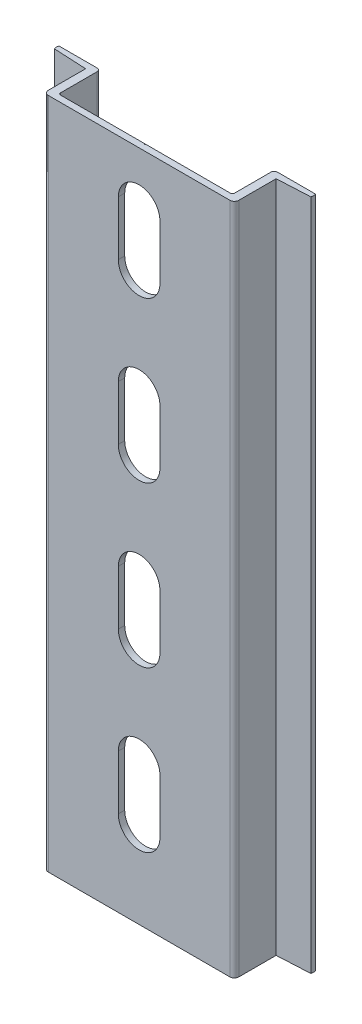
SolidWorks part; units mm, degrees
ref_plane "Alzado" through (0, 0, 0) normal (0, 0, 1) x (1, 0, 0)
ref_plane "Planta" through (0, 0, 0) normal (0, 1, 0) x (1, 0, 0)
ref_plane "Vista lateral" through (0, 0, 0) normal (1, 0, 0) x (0, 0, -1)
sketch "Croquis1" plane through (0, 0, 0) normal (0, 1, 0) x (1, 0, 0)
  line L0 (20.036, -8.0144) -> (20.036, 0) construction
  line L1 (34.92, -1.4884) -> (40.0721, -1.2268)
  line L3 (6.4521, -0.9884) -> (6.4521, -6.7144)
  line L4 (0, -0.4884) -> (5.9521, -0.4884)
  line L5 (5.8521, -8.0144) -> (34.22, -8.0144)
  line L6 (34.92, -1.4884) -> (34.92, -7.3144)
  line L8 (40.0721, -0.4884) -> (34.12, -0.4884)
  line L9 (33.62, -0.9884) -> (33.62, -6.7144)
  line L10 (5.1521, -1.4884) -> (5.1521, -7.3144)
  line L11 (6.7521, -7.0144) -> (33.32, -7.0144) construction
  line L12 (5.1521, -1.4884) -> (0, -1.2268)
  line L13 (6.7521, -7.0144) -> (33.32, -7.0144)
  arc A0 (34.22, -8.0144) -> (34.92, -7.3144) centre (34.22, -7.3144) ccw
  arc A1 (34.12, -0.4884) -> (33.62, -0.9884) centre (34.12, -0.9884) ccw
  arc A2 (33.32, -7.0144) -> (33.62, -6.7144) centre (33.32, -6.7144) ccw
  arc A3 (6.7521, -7.0144) -> (6.4521, -6.7144) centre (6.7521, -6.7144) cw
  arc A4 (5.9521, -0.4884) -> (6.4521, -0.9884) centre (5.9521, -0.9884) cw
  arc A5 (5.8521, -8.0144) -> (5.1521, -7.3144) centre (5.8521, -7.3144) cw
  spline S0 degree 2 poles (40.0721, -0.4884) (40.1909, -0.8585) (40.0721, -1.2268) knots 0 0 0 1 1 1
  spline S1 degree 2 poles (0, -0.4884) (-0.1188, -0.8585) (0, -1.2268) knots 0 0 0 1 1 1
extrude "Saliente-Extruir1" add sketch "Croquis1" along normal blind 105 and the other way blind 0.1
sketch "Croquis2" plane through (0, 0, 8.0144) normal (0, 0, 1) x (1, 0, 0)
  line L0 (20.036, -0.1) -> (20.036, 10) construction
  line L1 (5.8521, -0.1) -> (34.22, -0.1) construction
  line L2 (20.036, 25) -> (20.036, 35) construction
  line L3 (16.786, 38.25) -> (16.786, 46.75)
  line L4 (23.286, 38.25) -> (23.286, 46.75)
  line L5 (16.786, 13.25) -> (16.786, 21.75)
  line L6 (16.786, 63.25) -> (16.786, 71.75)
  line L7 (23.286, 13.25) -> (23.286, 21.75)
  line L8 (23.286, 63.25) -> (23.286, 71.75)
  line L9 (16.786, 88.25) -> (16.786, 96.75)
  line L10 (23.286, 88.25) -> (23.286, 96.75)
  line L11 (16.786, 113.25) -> (16.786, 121.75)
  line L12 (23.286, 113.25) -> (23.286, 121.75)
  line L13 (16.786, 138.25) -> (16.786, 146.75)
  line L14 (23.286, 138.25) -> (23.286, 146.75)
  line L15 (16.786, 163.25) -> (16.786, 171.75)
  line L16 (23.286, 163.25) -> (23.286, 171.75)
  line L17 (16.786, 188.25) -> (16.786, 196.75)
  line L18 (23.286, 188.25) -> (23.286, 196.75)
  arc A0 (23.286, 21.75) -> (16.786, 21.75) centre (20.036, 21.75) ccw
  arc A1 (16.786, 13.25) -> (23.286, 13.25) centre (20.036, 13.25) ccw
  arc A2 (23.286, 46.75) -> (16.786, 46.75) centre (20.036, 46.75) ccw
  arc A3 (16.786, 38.25) -> (23.286, 38.25) centre (20.036, 38.25) ccw
  arc A4 (23.286, 71.75) -> (16.786, 71.75) centre (20.036, 71.75) ccw
  arc A5 (16.786, 63.25) -> (23.286, 63.25) centre (20.036, 63.25) ccw
  arc A6 (23.286, 96.75) -> (16.786, 96.75) centre (20.036, 96.75) ccw
  arc A7 (16.786, 88.25) -> (23.286, 88.25) centre (20.036, 88.25) ccw
  arc A8 (23.286, 121.75) -> (16.786, 121.75) centre (20.036, 121.75) ccw
  arc A9 (16.786, 113.25) -> (23.286, 113.25) centre (20.036, 113.25) ccw
  arc A10 (23.286, 146.75) -> (16.786, 146.75) centre (20.036, 146.75) ccw
  arc A11 (16.786, 138.25) -> (23.286, 138.25) centre (20.036, 138.25) ccw
  arc A12 (23.286, 171.75) -> (16.786, 171.75) centre (20.036, 171.75) ccw
  arc A13 (16.786, 163.25) -> (23.286, 163.25) centre (20.036, 163.25) ccw
  arc A14 (23.286, 196.75) -> (16.786, 196.75) centre (20.036, 196.75) ccw
  arc A15 (16.786, 188.25) -> (23.286, 188.25) centre (20.036, 188.25) ccw
  point P10 (0, 0)
  dimension "D1" = 8
extrude "Cortar-Extruir4" cut sketch "Croquis2" against normal blind 10
sketch "Croquis4" plane through (0, 0, 7.0144) normal (0, 0, -1) x (-1, 0, 0)
  line L0 (-20.036, 10) -> (-20.036, -0.1) construction
  line L2 (-20.111, 24.95) -> (-19.961, 24.95)
  line L3 (-20.111, -0.05) -> (-19.961, -0.05)
  line L4 (-20.111, -0.05) -> (-20.111, 9.95)
  line L5 (-20.111, 9.95) -> (-19.961, 9.95)
  line L6 (-19.961, -0.05) -> (-19.961, 9.95)
  line L7 (-20.111, -0.05) -> (-19.961, 9.95) construction
  line L8 (-20.111, 9.95) -> (-19.961, -0.05) construction
  line L9 (-20.111, 24.95) -> (-20.111, 34.95)
  line L10 (-20.111, 34.95) -> (-19.961, 34.95)
  line L11 (-19.961, 24.95) -> (-19.961, 34.95)
  line L12 (-20.036, 35) -> (-20.036, 24.9) construction
  line L13 (-20.111, 24.95) -> (-19.961, 34.95) construction
  line L14 (-20.111, 34.95) -> (-19.961, 24.95) construction
  line L15 (-20.111, 49.95) -> (-19.961, 49.95)
  line L16 (-20.111, 49.95) -> (-20.111, 59.95)
  line L17 (-20.111, 59.95) -> (-19.961, 59.95)
  line L18 (-19.961, 49.95) -> (-19.961, 59.95)
  line L19 (-20.036, 60) -> (-20.036, 49.9) construction
  line L20 (-20.111, 49.95) -> (-19.961, 59.95) construction
  line L21 (-20.111, 59.95) -> (-19.961, 49.95) construction
  line L22 (-20.111, 74.95) -> (-19.961, 74.95)
  line L23 (-20.111, 74.95) -> (-20.111, 84.95)
  line L24 (-20.111, 84.95) -> (-19.961, 84.95)
  line L25 (-19.961, 74.95) -> (-19.961, 84.95)
  line L26 (-20.036, 85) -> (-20.036, 74.9) construction
  line L27 (-20.111, 74.95) -> (-19.961, 84.95) construction
  line L28 (-20.111, 84.95) -> (-19.961, 74.95) construction
  line L29 (-20.111, 99.95) -> (-19.961, 99.95)
  line L30 (-20.111, 99.95) -> (-20.111, 109.95)
  line L31 (-20.111, 109.95) -> (-19.961, 109.95)
  line L32 (-19.961, 99.95) -> (-19.961, 109.95)
  line L33 (-20.036, 110) -> (-20.036, 99.9) construction
  line L34 (-20.111, 99.95) -> (-19.961, 109.95) construction
  line L35 (-20.111, 109.95) -> (-19.961, 99.95) construction
  line L36 (-20.111, 124.95) -> (-19.961, 124.95)
  line L37 (-20.111, 124.95) -> (-20.111, 134.95)
  line L38 (-20.111, 134.95) -> (-19.961, 134.95)
  line L39 (-19.961, 124.95) -> (-19.961, 134.95)
  line L40 (-20.036, 135) -> (-20.036, 124.9) construction
  line L41 (-20.111, 124.95) -> (-19.961, 134.95) construction
  line L42 (-20.111, 134.95) -> (-19.961, 124.95) construction
  line L43 (-20.111, 149.95) -> (-19.961, 149.95)
  line L44 (-20.111, 149.95) -> (-20.111, 159.95)
  line L45 (-20.111, 159.95) -> (-19.961, 159.95)
  line L46 (-19.961, 149.95) -> (-19.961, 159.95)
  line L47 (-20.036, 160) -> (-20.036, 149.9) construction
  line L48 (-20.111, 149.95) -> (-19.961, 159.95) construction
  line L49 (-20.111, 159.95) -> (-19.961, 149.95) construction
  line L50 (-20.111, 174.95) -> (-19.961, 174.95)
  line L51 (-20.111, 174.95) -> (-20.111, 184.95)
  line L52 (-20.111, 184.95) -> (-19.961, 184.95)
  line L53 (-19.961, 174.95) -> (-19.961, 184.95)
  line L54 (-20.036, 185) -> (-20.036, 174.9) construction
  line L55 (-20.111, 174.95) -> (-19.961, 184.95) construction
  line L56 (-20.111, 184.95) -> (-19.961, 174.95) construction
  arc A0 (-23.286, 13.25) -> (-16.786, 13.25) centre (-20.036, 13.25) ccw construction
  point P6 (-20.036, 4.95)
  point P16 (-20.036, 29.95)
  point P23 (-20.036, 54.95)
  point P30 (-20.036, 79.95)
  point P37 (-20.036, 104.95)
  point P44 (-20.036, 129.95)
  point P51 (-20.036, 154.95)
  point P58 (-20.036, 179.95)
  dimension "D1" = 8
extrude "Cortar-Extruir9" cut sketch "Croquis4" against normal blind 0.1
